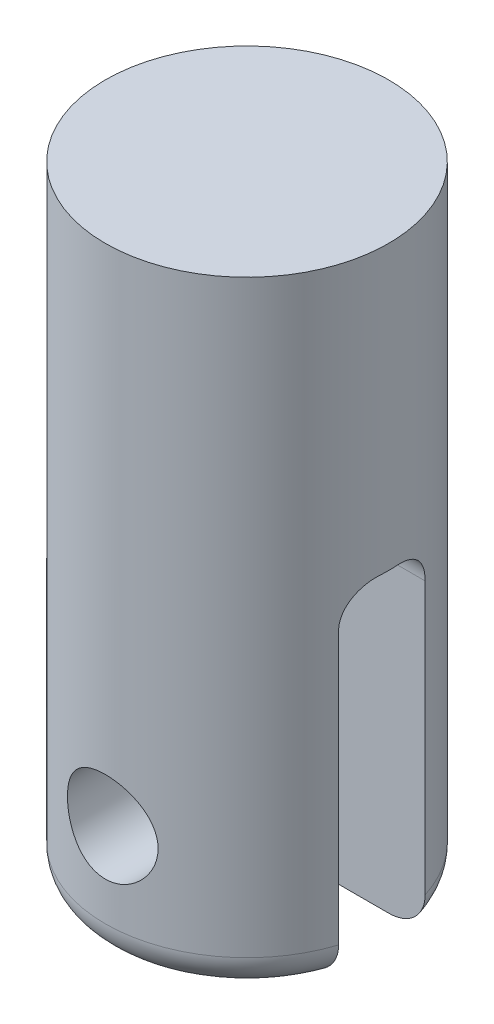
SolidWorks part; units mm, degrees
ref_plane "Спереди" through (0, 0, 0) normal (0, 0, 1) x (1, 0, 0)
ref_plane "Сверху" through (0, 0, 0) normal (0, 1, 0) x (1, 0, 0)
ref_plane "Справа" through (0, 0, 0) normal (1, 0, 0) x (0, 0, -1)
sketch "Эскиз1" plane through (0, 0, 0) normal (0, 1, 0) x (1, 0, 0)
  circle A0 centre (0, 0) radius 12.5
extrude "Вытянуть1" add sketch "Эскиз1" along normal blind 55 from offset 15
sketch "Эскиз2" plane through (0, 0, 0) normal (1, 0, 0) x (0, 0, -1)
  line L0 (-12.5, -15) -> (12.5, -15) construction
  line L1 (-3.8177, 15) -> (3.8177, 15)
  line L2 (-3.8177, 15) -> (-3.8177, -15)
  line L3 (-3.8177, -15) -> (3.8177, -15)
  line L4 (3.8177, 15) -> (3.8177, -15)
  line L5 (-3.8177, 15) -> (3.8177, -15) construction
  line L6 (-3.8177, -15) -> (3.8177, 15) construction
  point P0 (0, 0)
  dimension "D1" = 30
extrude "Вытянуть2" cut sketch "Эскиз2" against normal mid plane 50
fillet "Скругление1" radius 3 2 edges at (0, -15, -12.5) (0, -15, 12.5)
sketch "Эскиз3" plane through (0, 0, 0) normal (0, 0, 1) x (1, 0, 0)
  circle A0 centre (0, -4.5817) radius 4
extrude "Вытянуть3" cut sketch "Эскиз3" against normal mid plane 50
fillet "Скругление2" radius 3 2 edges at (0, 15, 3.8177) (0, 15, -3.8177)
